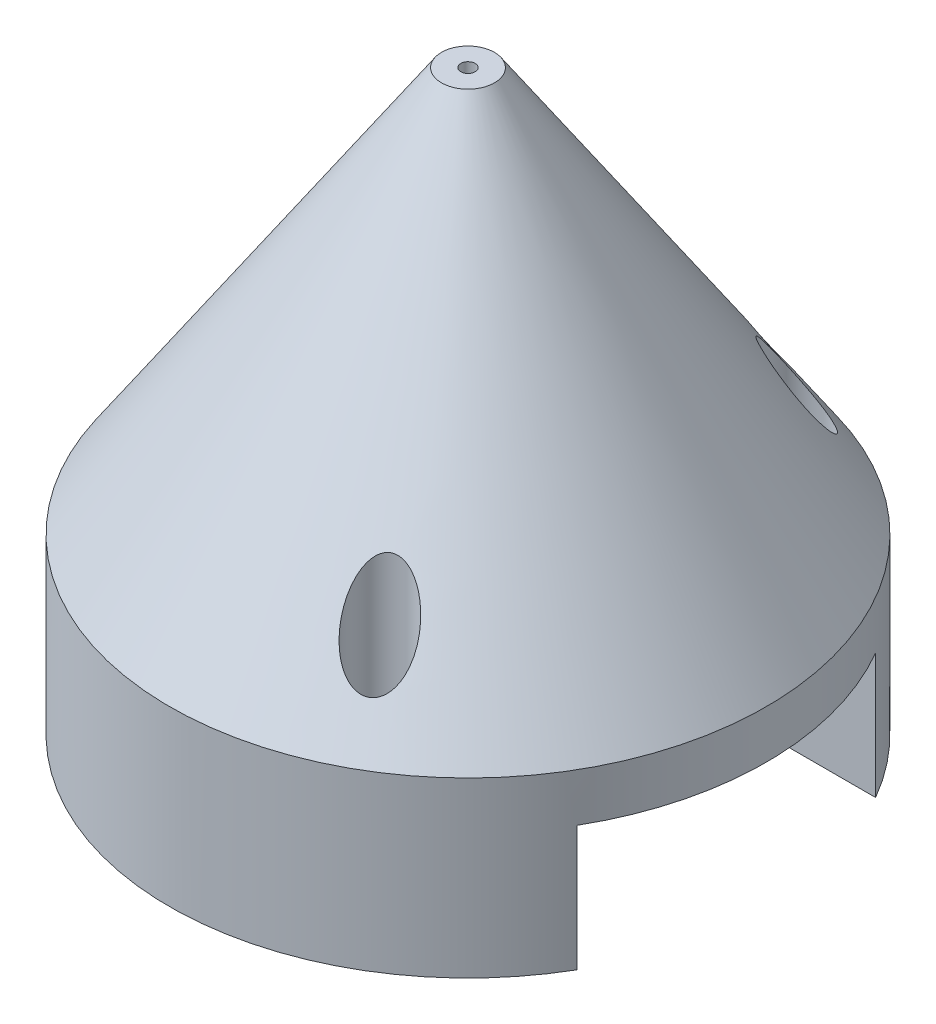
SolidWorks part; units mm, degrees
material "Nylon 6/10"
ref_plane "Front Plane" through (0, 0, 0) normal (0, 0, 1) x (1, 0, 0)
ref_plane "Top Plane" through (0, 0, 0) normal (0, 1, 0) x (1, 0, 0)
ref_plane "Right Plane" through (0, 0, 0) normal (1, 0, 0) x (0, 0, -1)
sketch "Sketch1" plane through (0, 0, 0) normal (0, 0, 1) x (1, 0, 0)
  line L0 (-5.4748, 60) -> (-33.7248, 18)
  line L1 (-33.7248, 18) -> (-33.7248, 0)
  line L2 (-33.7248, 0) -> (-22.7248, 0)
  line L3 (-2.7248, 66.8317) -> (-2.7248, -1.4804) construction
  line L4 (-3.4748, 60) -> (-3.4748, 13)
  line L5 (-22.7248, 0) -> (-22.7248, 13)
  line L6 (-22.7248, 13) -> (-3.4748, 13)
  line L7 (-5.4748, 60) -> (-3.4748, 60)
  dimension "D1" = 62
  dimension "D2" = 18
  dimension "D4" = 1.5
  dimension "D5" = 40
  dimension "D6" = 13
  dimension "D7" = 11
  dimension "D8" = 2
  dimension "D9" = 60
revolve "Revolve1" add sketch "Sketch1" angle 360 about L3
sketch "Sketch2" plane through (0, 0, 0) normal (0, -1, 0) x (1, 0, 0)
  line L0 (-2.7248, 0) -> (3.9648, 0) construction
  line L1 (3.9648, 15.5) -> (44.1012, 15.5)
  line L2 (3.9648, 15.5) -> (3.9648, -15.5)
  line L3 (3.9648, -15.5) -> (44.1012, -15.5)
  line L4 (44.1012, 15.5) -> (44.1012, -15.5)
  dimension "D1" = 31
extrude "Cut-Extrude1" cut sketch "Sketch2" against normal up to surface (13 mm away) up to face at (-3.4748, 13, 0)
ref_plane "Plane1" through (0, 18, 0) normal (0, 1, 0) x (-1, 0, 0)
sketch "Sketch3" plane through (0, 18, 0) normal (0, 1, 0) x (-1, 0, 0)
  circle A0 centre (2.7248, 0) radius 25
  dimension "D1" = 50
extrude "Cut-Extrude2" [suppressed] cut sketch "Sketch3" along normal blind 10 flip side to cut
sketch "Sketch4" plane through (0, 18, 0) normal (0, 1, 0) x (-1, 0, 0)
  circle A0 centre (2.7248, 0) radius 25 construction
  circle A1 centre (27.7248, 0) radius 3
  dimension "D1" = 50
  dimension "D2" = 6
extrude "Cut-Extrude3" cut sketch "Sketch4" against normal blind 10 and the other way through all
sketch "Sketch5" plane through (0, 8, 0) normal (0, 1, 0) x (1, 0, 0)
  circle A0 centre (-27.7248, 0) radius 1.6
  dimension "D1" = 3.2
extrude "Cut-Extrude4" cut sketch "Sketch5" against normal through all
pattern_circular "CirPattern1" count 3 over 360 about axis through (-2.7248, 0, 0) along (0, 1, 0) of "Cut-Extrude3", "Cut-Extrude4"
chamfer "Chamfer1" distance 2.5 angle 30 1 edges at (-3.4748, 13, 0)
